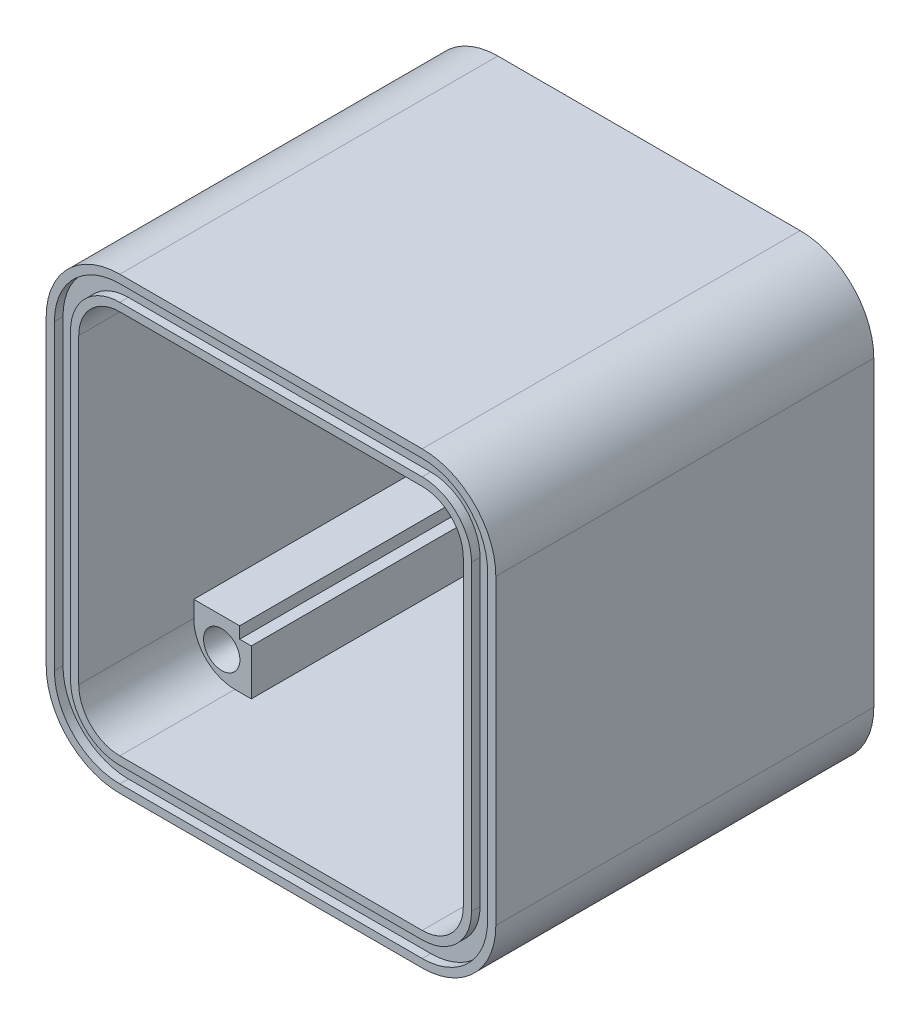
SolidWorks part; units mm, degrees
material "ABS"
ref_plane "X-Y Datum" through (0, 0, 0) normal (0, 0, 1) x (1, 0, 0)
ref_plane "X-Z Datum" through (0, 0, 0) normal (0, 1, 0) x (1, 0, 0)
ref_plane "Y-Z Datum" through (0, 0, 0) normal (1, 0, 0) x (0, 0, -1)
sketch "Sketch1" plane through (0, 0, 0) normal (0, 0, 1) x (1, 0, 0)
  line L0 (-32.258, -32.258) -> (-32.258, -11.938)
  line L1 (32.258, 32.258) -> (-32.258, 32.258)
  line L2 (32.258, 32.258) -> (32.258, -32.258)
  line L3 (32.258, -32.258) -> (-32.258, -32.258)
  line L5 (32.258, 32.258) -> (-32.258, -32.258) construction
  line L6 (32.258, -32.258) -> (-32.258, 32.258) construction
  line L7 (55.1739, 0) -> (-55.1739, 0) construction
  line L8 (-32.258, 32.258) -> (-32.258, 11.938)
  line L9 (-32.258, 11.938) -> (-32.258, -11.938)
  arc A0 (-32.258, -11.938) -> (-32.258, 11.938) centre (-9.8383, 0) cw construction
  point P0 (0, 0)
  dimension "D2" = 25.4
  dimension "D1" = 64.516
  dimension "D3" = 20.32
extrude "Boss-Extrude1" add sketch "Sketch1" along normal mid plane 58.42
shell "Shell1" thickness 2.54
fillet "Fillet1" radius 6.35 8 edges at (32.258, 32.258, 0) (32.258, -32.258, 0) (-32.258, -32.258, 0) (-32.258, 32.258, 0) (29.718, 29.718, 1.27) (29.718, -29.718, 1.27) (-29.718, -29.718, 1.27) (-29.718, 29.718, 1.27)
sketch "Sketch2" plane through (0, 0, -26.67) normal (0, 0, 1) x (1, 0, 0)
  line L0 (55.1739, 0) -> (-55.1739, 0) construction
  line L1 (-23.368, 29.718) -> (-20.828, 29.718)
  line L8 (-29.718, -20.828) -> (-20.828, -20.828)
  line L9 (-29.718, 20.828) -> (-29.718, 23.368)
  line L15 (-20.828, -29.718) -> (-20.828, -20.828)
  line L16 (29.718, -23.368) -> (29.718, 23.368)
  line L17 (23.368, 29.718) -> (-23.368, 29.718)
  line L18 (-29.718, 23.368) -> (-29.718, -23.368)
  line L20 (-23.368, -29.718) -> (23.368, -29.718)
  line L25 (-23.368, -29.718) -> (-20.828, -29.718)
  line L26 (-20.828, 29.718) -> (-20.828, 20.828)
  line L27 (-29.718, 20.828) -> (-20.828, 20.828)
  line L28 (0, -43.0151) -> (0, 43.0151) construction
  line L29 (29.718, 20.828) -> (20.828, 20.828)
  line L30 (20.828, 29.718) -> (20.828, 20.828)
  line L31 (23.368, -29.718) -> (20.828, -29.718)
  line L32 (29.718, -20.828) -> (29.718, -23.368)
  line L33 (20.828, -29.718) -> (20.828, -20.828)
  line L34 (29.718, 20.828) -> (29.718, 23.368)
  line L35 (29.718, -20.828) -> (20.828, -20.828)
  line L36 (23.368, 29.718) -> (20.828, 29.718)
  arc A9 (-29.718, 23.368) -> (-23.368, 29.718) centre (-23.368, 23.368) cw
  arc A10 (29.718, 23.368) -> (23.368, 29.718) centre (23.368, 23.368) ccw
  arc A19 (-23.368, 29.718) -> (-29.718, 23.368) centre (-23.368, 23.368) ccw
  arc A21 (-29.718, -23.368) -> (-23.368, -29.718) centre (-23.368, -23.368) ccw
  arc A22 (23.368, -29.718) -> (29.718, -23.368) centre (23.368, -23.368) ccw
  arc A26 (-29.718, -23.368) -> (-23.368, -29.718) centre (-23.368, -23.368) ccw
  arc A27 (29.718, -23.368) -> (23.368, -29.718) centre (23.368, -23.368) cw
  arc A28 (29.718, 23.368) -> (23.368, 29.718) centre (23.368, 23.368) ccw
  line M7 (-23.368, -29.718) -> (23.368, -29.718)
  line M12 (-29.718, 23.368) -> (-29.718, -23.368)
  arc M22 (-29.718, -23.368) -> (-23.368, -29.718) centre (-23.368, -23.368) ccw
  dimension "D2" = 8.89
  dimension "D1" = 0
extrude "Boss-Extrude2" add sketch "Sketch2" along normal blind 38.1 contours L15 L8 M7 M12 M22 | A9 L1 L26 L27 L9 | A28 L36 L30 L29 L34 | A27 L31 L33 L35 L32
sketch "Sketch4" [suppressed] plane through (0, 0, 11.43) normal (0, 0, 1) x (1, 0, 0)
  line L0 (-20.828, -29.718) -> (-20.828, -20.828) construction
  line L1 (-20.828, -22.5) -> (-20.828, -20.828)
  line L2 (-20.828, -20.828) -> (-29.718, -20.828) construction
  line L3 (-20.828, -20.828) -> (-22.648, -20.828)
  line L4 (-22.648, -18) -> (-22.648, -22.5) construction
  line L5 (-22.648, -20.828) -> (-22.648, -22.5)
  line L6 (-22.648, -22.5) -> (22.352, -22.5) construction
  line L7 (-22.648, -22.5) -> (-20.828, -22.5)
  line L8 (-22.648, 22.5) -> (-22.648, 17) construction
  line L9 (-22.648, 22.5) -> (-22.648, 20.828)
  line L10 (-22.648, 22.5) -> (22.352, 22.5) construction
  line L11 (-22.648, 22.5) -> (-20.828, 22.5)
  line L12 (-20.828, 20.828) -> (-20.828, 29.718) construction
  line L13 (-20.828, 20.828) -> (-20.828, 22.5)
  line L14 (-29.718, 20.828) -> (-20.828, 20.828) construction
  line L15 (-22.648, 20.828) -> (-20.828, 20.828)
  line L16 (20.828, 20.828) -> (29.718, 20.828) construction
  line L17 (22.352, 22.5) -> (22.352, 11.7) construction
  line L18 (20.828, 29.718) -> (20.828, 20.828) construction
  line L19 (20.828, 20.828) -> (22.352, 20.828)
  line L20 (22.352, 22.5) -> (22.352, 20.828)
  line L21 (20.828, 22.5) -> (20.828, 20.828)
  line L22 (22.352, -13.5) -> (22.352, -22.5) construction
  line L23 (20.828, -20.828) -> (20.828, -29.718) construction
  line L24 (29.718, -20.828) -> (20.828, -20.828) construction
  line L25 (-22.648, -22.5) -> (-20.828, -22.5)
  line L26 (22.352, -20.828) -> (22.352, -22.5)
  line L27 (20.828, -20.828) -> (20.828, -22.5)
  line L28 (22.352, -20.828) -> (20.828, -20.828)
  line L29 (20.828, -22.5) -> (22.352, -22.5)
  line L30 (20.828, 22.5) -> (22.352, 22.5)
extrude "Cut-Extrude4" [suppressed] cut sketch "Sketch4" against normal up to surface (38.1 mm away)
sketch "Sketch3" plane through (0, 0, 11.43) normal (0, 0, 1) x (1, 0, 0)
  line L0 (-25.908, -32.258) -> (25.908, -32.258) construction
  line L4 (-32.258, 25.908) -> (-32.258, -25.908) construction
  line L5 (55.1739, 0) -> (-55.1739, 0) construction
  line L6 (0, -43.0151) -> (0, 43.0151) construction
  circle A0 centre (-25.4, -25.4) radius 2.8067
  circle A1 centre (-25.4, 25.4) radius 2.8067
  circle A2 centre (25.4, 25.4) radius 2.8067
  circle A3 centre (25.4, -25.4) radius 2.8067
  dimension "D1" = 6.858
  dimension "D3" = 5.6134
  dimension "D2" = 6.858
extrude "Cut-Extrude1" cut sketch "Sketch3" against normal blind 4.7 draft 8
sketch "Sketch5" plane through (0, 0, 11.43) normal (0, 0, 1) x (1, 0, 0)
  line L1 (-22.627, -22.627) -> (22.627, -22.627)
  line L2 (-22.627, -22.627) -> (-22.627, 22.627)
  line L3 (-22.627, 22.627) -> (22.627, 22.627)
  line L4 (22.627, -22.627) -> (22.627, 22.627)
  line L5 (-22.627, -22.627) -> (22.627, 22.627) construction
  line L6 (-22.627, 22.627) -> (22.627, -22.627) construction
  point P0 (0, 0)
extrude "Cut-Extrude5" cut sketch "Sketch5" against normal up to surface (38.1 mm away) up to face at (0, 0, -26.67)
sketch "Sketch6" plane through (0, 0, 29.21) normal (0, 0, 1) x (1, 0, 0)
  line L151 (23.368, 29.718) -> (20.828, 29.718)
  line L152 (20.828, 29.718) -> (-20.828, 29.718)
  line L153 (-20.828, 29.718) -> (-23.368, 29.718)
  line L154 (-29.718, 23.368) -> (-29.718, -23.368)
  line L155 (-23.368, -29.718) -> (-20.828, -29.718)
  line L156 (-20.828, -29.718) -> (20.828, -29.718)
  line L157 (20.828, -29.718) -> (23.368, -29.718)
  line L158 (29.718, -23.368) -> (29.718, 23.368)
  line L159 (23.368, 30.988) -> (20.828, 30.988)
  line L160 (30.988, -23.368) -> (30.988, 23.368)
  line L161 (20.828, -30.988) -> (23.368, -30.988)
  line L162 (-23.368, -30.988) -> (-20.828, -30.988)
  line L163 (-20.828, -30.988) -> (20.828, -30.988)
  line L164 (-30.988, 23.368) -> (-30.988, -23.368)
  line L165 (-20.828, 30.988) -> (-23.368, 30.988)
  line L166 (20.828, 30.988) -> (-20.828, 30.988)
  line L167 (23.368, 30.988) -> (20.828, 30.988)
  line L168 (30.988, -23.368) -> (30.988, 23.368)
  line L169 (20.828, -30.988) -> (23.368, -30.988)
  line L170 (-23.368, -30.988) -> (-20.828, -30.988)
  line L171 (-20.828, -30.988) -> (20.828, -30.988)
  line L172 (-30.988, 23.368) -> (-30.988, -23.368)
  line L173 (-20.828, 30.988) -> (-23.368, 30.988)
  line L174 (20.828, 30.988) -> (-20.828, 30.988)
  arc A65 (-23.368, 29.718) -> (-29.718, 23.368) centre (-23.368, 23.368) ccw
  arc A66 (-29.718, -23.368) -> (-23.368, -29.718) centre (-23.368, -23.368) ccw
  arc A67 (23.368, -29.718) -> (29.718, -23.368) centre (23.368, -23.368) ccw
  arc A68 (29.718, 23.368) -> (23.368, 29.718) centre (23.368, 23.368) ccw
  arc A69 (30.988, 23.368) -> (23.368, 30.988) centre (23.368, 23.368) ccw
  arc A70 (23.368, -30.988) -> (30.988, -23.368) centre (23.368, -23.368) ccw
  arc A71 (-30.988, -23.368) -> (-23.368, -30.988) centre (-23.368, -23.368) ccw
  arc A72 (-23.368, 30.988) -> (-30.988, 23.368) centre (-23.368, 23.368) ccw
  arc A73 (30.988, 23.368) -> (23.368, 30.988) centre (23.368, 23.368) ccw
  arc A74 (23.368, -30.988) -> (30.988, -23.368) centre (23.368, -23.368) ccw
  arc A75 (-30.988, -23.368) -> (-23.368, -30.988) centre (-23.368, -23.368) ccw
  arc A76 (-23.368, 30.988) -> (-30.988, 23.368) centre (-23.368, 23.368) ccw
  dimension "D1" = 1.27
  dimension "D2" = 1.27
extrude "Cut-Extrude6" cut sketch "Sketch6" against normal blind 1.3208 flip side to cut
sketch "Sketch7" plane through (0, 0, -26.67) normal (0, 0, 1) x (1, 0, 0)
  line L27 (23.368, 32.2072) -> (-23.368, 32.2072)
  line L28 (-32.2072, 23.368) -> (-32.2072, -23.368)
  line L29 (-23.368, -32.2072) -> (23.368, -32.2072)
  line L30 (32.2072, -23.368) -> (32.2072, 23.368)
  line L31 (33.4772, -23.368) -> (33.4772, 23.368)
  line L32 (-23.368, -33.4772) -> (23.368, -33.4772)
  line L33 (-33.4772, 23.368) -> (-33.4772, -23.368)
  line L34 (23.368, 33.4772) -> (-23.368, 33.4772)
  line L35 (33.4772, -23.368) -> (33.4772, 23.368)
  line L36 (-23.368, -33.4772) -> (23.368, -33.4772)
  line L37 (-33.4772, 23.368) -> (-33.4772, -23.368)
  line L38 (23.368, 33.4772) -> (-23.368, 33.4772)
  arc A23 (32.2072, 23.368) -> (23.368, 32.2072) centre (23.368, 23.368) ccw
  arc A24 (-23.368, 32.2072) -> (-32.2072, 23.368) centre (-23.368, 23.368) ccw
  arc A25 (-32.2072, -23.368) -> (-23.368, -32.2072) centre (-23.368, -23.368) ccw
  arc A26 (23.368, -32.2072) -> (32.2072, -23.368) centre (23.368, -23.368) ccw
  arc A27 (33.4772, 23.368) -> (23.368, 33.4772) centre (23.368, 23.368) ccw
  arc A28 (23.368, -33.4772) -> (33.4772, -23.368) centre (23.368, -23.368) ccw
  arc A29 (-33.4772, -23.368) -> (-23.368, -33.4772) centre (-23.368, -23.368) ccw
  arc A30 (-23.368, 33.4772) -> (-33.4772, 23.368) centre (-23.368, 23.368) ccw
  arc A31 (33.4772, 23.368) -> (23.368, 33.4772) centre (23.368, 23.368) ccw
  arc A32 (23.368, -33.4772) -> (33.4772, -23.368) centre (23.368, -23.368) ccw
  arc A33 (-33.4772, -23.368) -> (-23.368, -33.4772) centre (-23.368, -23.368) ccw
  arc A34 (-23.368, 33.4772) -> (-33.4772, 23.368) centre (-23.368, 23.368) ccw
  dimension "D1" = 2.4892
  dimension "D2" = 1.27
extrude "Boss-Extrude3" add sketch "Sketch7" along normal up to surface and the other way up to surface
sketch "Sketch9" plane through (0, 0, 27.8892) normal (0, 0, 1) x (1, 0, 0)
  line L21 (23.368, 33.4772) -> (-23.368, 33.4772)
  line L22 (-33.4772, 23.368) -> (-33.4772, -23.368)
  line L23 (-23.368, -33.4772) -> (23.368, -33.4772)
  line L24 (33.4772, -23.368) -> (33.4772, 23.368)
  line L25 (34.7472, -23.368) -> (34.7472, 23.368)
  line L26 (-23.368, -34.7472) -> (23.368, -34.7472)
  line L27 (-34.7472, 23.368) -> (-34.7472, -23.368)
  line L28 (23.368, 34.7472) -> (-23.368, 34.7472)
  line L29 (34.7472, -23.368) -> (34.7472, 23.368)
  line L30 (-23.368, -34.7472) -> (23.368, -34.7472)
  line L31 (-34.7472, 23.368) -> (-34.7472, -23.368)
  line L32 (23.368, 34.7472) -> (-23.368, 34.7472)
  arc A16 (33.4772, 23.368) -> (23.368, 33.4772) centre (23.368, 23.368) ccw
  arc A17 (-23.368, 33.4772) -> (-33.4772, 23.368) centre (-23.368, 23.368) ccw
  arc A18 (-33.4772, -23.368) -> (-23.368, -33.4772) centre (-23.368, -23.368) ccw
  arc A19 (23.368, -33.4772) -> (33.4772, -23.368) centre (23.368, -23.368) ccw
  arc A20 (34.7472, 23.368) -> (23.368, 34.7472) centre (23.368, 23.368) ccw
  arc A21 (23.368, -34.7472) -> (34.7472, -23.368) centre (23.368, -23.368) ccw
  arc A22 (-34.7472, -23.368) -> (-23.368, -34.7472) centre (-23.368, -23.368) ccw
  arc A23 (-23.368, 34.7472) -> (-34.7472, 23.368) centre (-23.368, 23.368) ccw
  arc A24 (34.7472, 23.368) -> (23.368, 34.7472) centre (23.368, 23.368) ccw
  arc A25 (23.368, -34.7472) -> (34.7472, -23.368) centre (23.368, -23.368) ccw
  arc A26 (-34.7472, -23.368) -> (-23.368, -34.7472) centre (-23.368, -23.368) ccw
  arc A27 (-23.368, 34.7472) -> (-34.7472, 23.368) centre (-23.368, 23.368) ccw
  dimension "D1" = 1.27
  dimension "D2" = 1.27
extrude "Boss-Extrude7" add sketch "Sketch9" along normal up to surface and the other way up to surface
